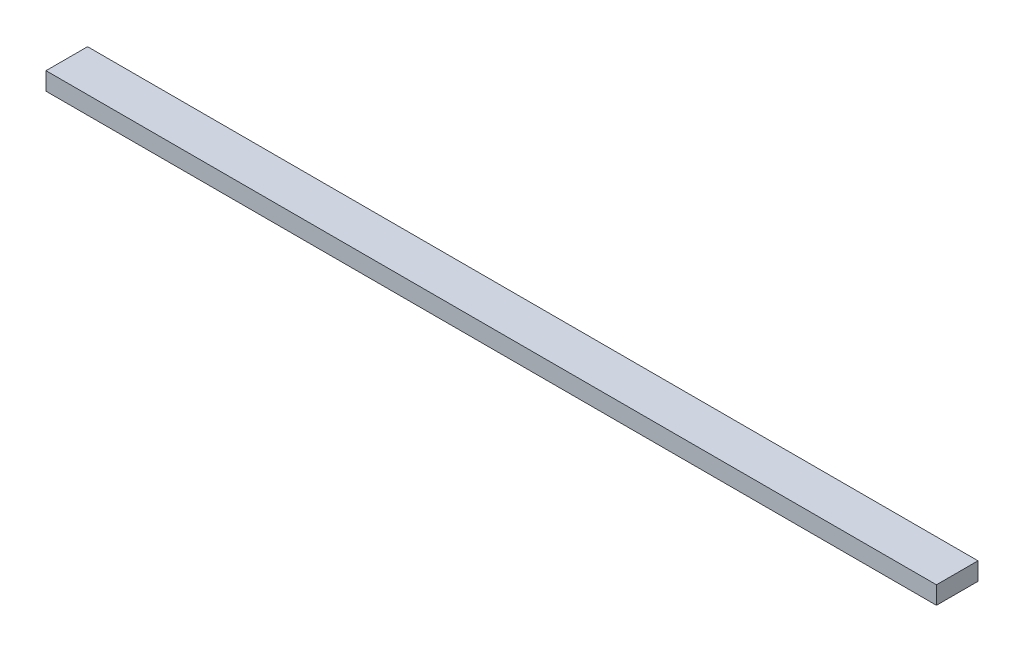
SolidWorks part; units mm, degrees
material "Pine"
ref_plane "Front Plane" through (0, 0, 0) normal (0, 0, 1) x (1, 0, 0)
ref_plane "Top Plane" through (0, 0, 0) normal (0, 1, 0) x (1, 0, 0)
ref_plane "Right Plane" through (0, 0, 0) normal (1, 0, 0) x (0, 0, -1)
sketch "Sketch1" plane through (0, 0, 0) normal (1, 0, 0) x (0, 0, -1)
  line L1 (-22.225, -9.525) -> (22.225, -9.525)
  line L2 (-22.225, -9.525) -> (-22.225, 9.525)
  line L3 (-22.225, 9.525) -> (22.225, 9.525)
  line L4 (22.225, -9.525) -> (22.225, 9.525)
  line L5 (-22.225, -9.525) -> (22.225, 9.525) construction
  line L6 (-22.225, 9.525) -> (22.225, -9.525) construction
  point P0 (0, 0)
  dimension "D1" = 44.45
  dimension "D2" = 19.05
extrude "Boss-Extrude1" add sketch "Sketch1" along normal mid plane 952.5
